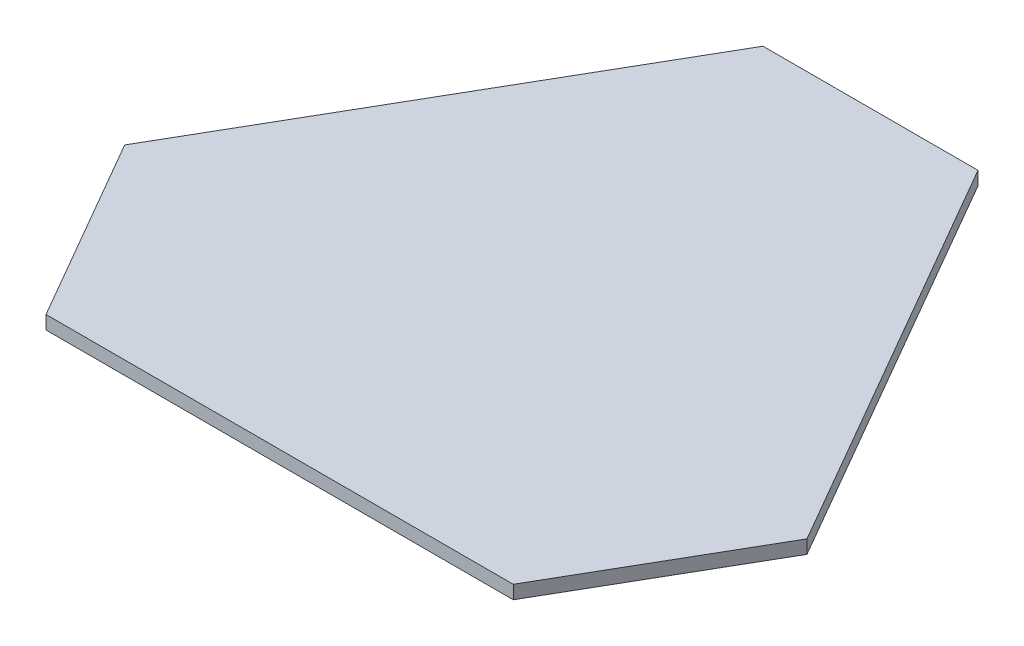
SolidWorks part; units mm, degrees
ref_plane "Front Plane" through (0, 0, 0) normal (0, 0, 1) x (1, 0, 0)
ref_plane "Top Plane" through (0, 0, 0) normal (0, 1, 0) x (1, 0, 0)
ref_plane "Right Plane" through (0, 0, 0) normal (1, 0, 0) x (0, 0, -1)
sketch "Sketch1" plane through (0, 0, 0) normal (0, 1, 0) x (1, 0, 0)
  line L0 (0.1949, 62.7522) -> (40.1949, 62.7522)
  line L1 (40.1949, 62.7522) -> (83.6624, -12.5357)
  line L2 (63.6624, -47.1767) -> (83.6624, -12.5357)
  line L3 (63.6624, -47.1767) -> (-23.2726, -47.1767)
  line L4 (-23.2726, -47.1767) -> (-43.2726, -12.5357)
  line L5 (-43.2726, -12.5357) -> (0.1949, 62.7522)
  dimension "D1" = 120
  dimension "D2" = 120
  dimension "D3" = 120
  dimension "D4" = 120
  dimension "D5" = 120
  dimension "D6" = 120
  dimension "D7" = 40
  dimension "D8" = 40
  dimension "D9" = 86.9349
  dimension "D10" = 86.9349
  dimension "D11" = 86.9349
extrude "Boss-Extrude1" add sketch "Sketch1" against normal blind 2.5
